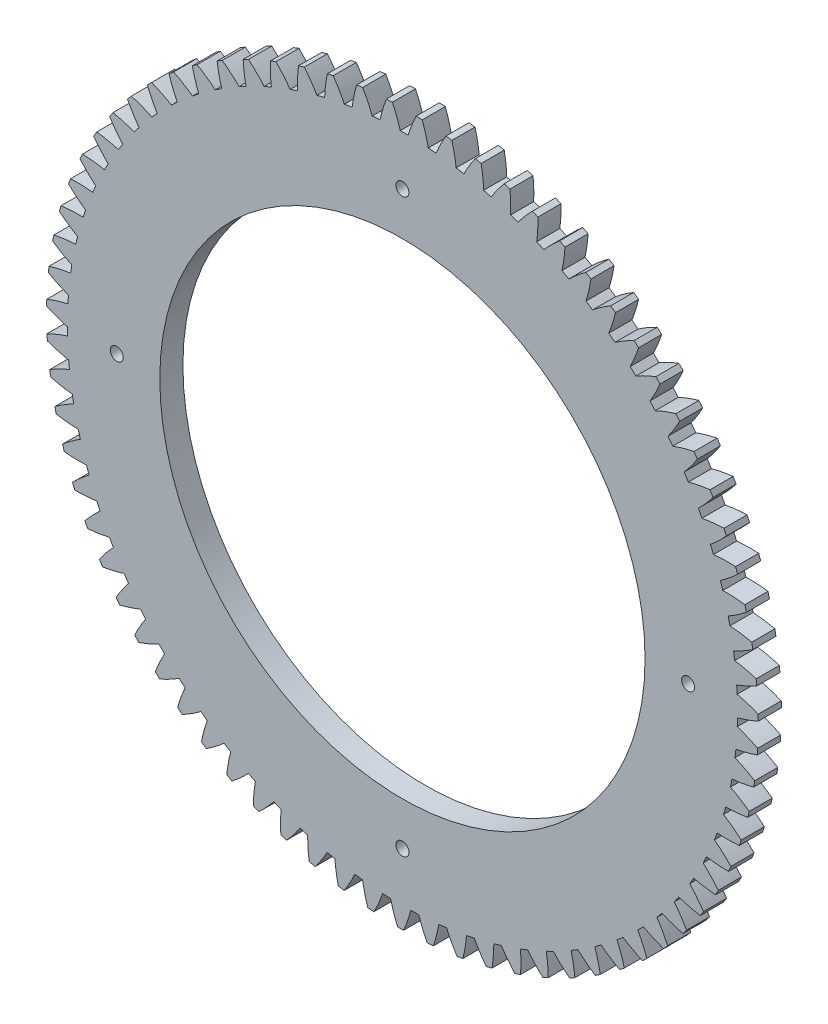
SolidWorks part; units mm, degrees
ref_plane "Front Plane" through (0, 0, 0) normal (0, 0, 1) x (1, 0, 0)
ref_plane "Top Plane" through (0, 0, 0) normal (0, 1, 0) x (1, 0, 0)
ref_plane "Right Plane" through (0, 0, 0) normal (1, 0, 0) x (0, 0, -1)
sketch "Sketch1" plane through (0, 0, 0) normal (0, 0, 1) x (1, 0, 0)
  circle A0 centre (0, 0) radius 78.5 construction
  circle A1 centre (0, 78.5) radius 1.7859
  circle A2 centre (78.5, 0) radius 1.7859
  circle A3 centre (0, -78.5) radius 1.7859
  circle A4 centre (-78.5, 0) radius 1.7859
  point P14 (0, 0)
  circle B0 centre (0, 0) radius 66.675
  arc B1 (-97.7746, 1.7328) -> (-92.073, -0.3661) centre (-81.8037, 36.3238) ccw
  arc B2 (-92.073, -0.3661) -> (-92.039, -2.5301) centre (0, 0) ccw
  arc B3 (-92.039, -2.5301) -> (-97.6718, -4.8073) centre (-80.6208, -38.8788) ccw
  arc B4 (-97.6718, -4.8073) -> (-97.5767, -6.4549) centre (0, 0) ccw
  arc B5 (-97.5767, -6.4549) -> (-91.7195, -8.0693) centre (-84.5564, 29.3513) ccw
  arc B6 (-91.7195, -8.0693) -> (-91.5045, -10.2228) centre (0, 0) ccw
  arc B7 (-91.5045, -10.2228) -> (-96.927, -12.9634) centre (-77.0847, -45.4887) ccw
  arc B8 (-96.927, -12.9634) -> (-96.6944, -14.5972) centre (0, 0) ccw
  arc B9 (-96.6944, -14.5972) -> (-90.7226, -15.7159) centre (-86.7159, 22.1729) ccw
  arc B10 (-90.7226, -15.7159) -> (-90.3281, -17.8438) centre (0, 0) ccw
  arc B11 (-90.3281, -17.8438) -> (-95.5023, -21.0285) centre (-73.008, -51.7794) ccw
  arc B12 (-95.5023, -21.0285) -> (-95.1338, -22.6372) centre (0, 0) ccw
  arc B13 (-95.1338, -22.6372) -> (-89.0893, -23.2522) centre (-88.2671, 14.8389) ccw
  arc B14 (-89.0893, -23.2522) -> (-88.5182, -25.3397) centre (0, 0) ccw
  arc B15 (-88.5182, -25.3397) -> (-93.4077, -28.9462) centre (-68.4191, -57.707) ccw
  arc B16 (-93.4077, -28.9462) -> (-92.9059, -30.5184) centre (0, 0) ccw
  arc B17 (-92.9059, -30.5184) -> (-86.8312, -30.6255) centre (-89.1992, 7.4009) ccw
  arc B18 (-86.8312, -30.6255) -> (-86.0874, -32.6579) centre (0, 0) ccw
  arc B19 (-86.0874, -32.6579) -> (-90.658, -36.6608) centre (-63.3504, -63.2298) ccw
  arc B20 (-90.658, -36.6608) -> (-90.0264, -38.1855) centre (0, 0) ccw
  arc B21 (-90.0264, -38.1855) -> (-83.964, -37.7839) centre (-89.5057, -0.0891) ccw
  arc B22 (-83.964, -37.7839) -> (-83.0527, -39.7469) centre (0, 0) ccw
  arc B23 (-83.0527, -39.7469) -> (-87.2723, -44.1183) centre (-57.8373, -68.309) ccw
  arc B24 (-87.2723, -44.1183) -> (-86.5154, -45.5848) centre (0, 0) ccw
  arc B25 (-86.5154, -45.5848) -> (-80.5078, -44.6773) centre (-89.1843, -7.5784) ccw
  arc B26 (-80.5078, -44.6773) -> (-79.4355, -46.5572) centre (0, 0) ccw
  arc B27 (-79.4355, -46.5572) -> (-83.2745, -51.2664) centre (-51.9185, -72.9092) ccw
  arc B28 (-83.2745, -51.2664) -> (-82.3975, -52.6644) centre (0, 0) ccw
  arc B29 (-82.3975, -52.6644) -> (-76.487, -51.2574) centre (-88.2374, -15.0146) ccw
  arc B30 (-76.487, -51.2574) -> (-75.2611, -53.0409) centre (0, 0) ccw
  arc B31 (-75.2611, -53.0409) -> (-78.6926, -58.0548) centre (-45.6355, -76.9979) ccw
  arc B32 (-78.6926, -58.0548) -> (-77.7017, -59.3745) centre (0, 0) ccw
  arc B33 (-77.7017, -59.3745) -> (-71.9296, -57.4779) centre (-86.6715, -22.3455) ccw
  arc B34 (-71.9296, -57.4779) -> (-70.5588, -59.1526) centre (0, 0) ccw
  arc B35 (-70.5588, -59.1526) -> (-73.5587, -64.436) centre (-39.0325, -80.5465) ccw
  arc B36 (-73.5587, -64.436) -> (-72.4608, -65.6682) centre (0, 0) ccw
  arc B37 (-72.4608, -65.6682) -> (-66.8677, -63.2952) centre (-84.4977, -29.5196) ccw
  arc B38 (-66.8677, -63.2952) -> (-65.3616, -64.8493) centre (0, 0) ccw
  arc B39 (-65.3616, -64.8493) -> (-67.9089, -70.3653) centre (-32.1556, -83.5302) ccw
  arc B40 (-67.9089, -70.3653) -> (-66.7117, -71.5013) centre (0, 0) ccw
  arc B41 (-66.7117, -71.5013) -> (-61.3368, -68.6686) centre (-81.7313, -36.4866) ccw
  arc B42 (-61.3368, -68.6686) -> (-59.7059, -70.0912) centre (0, 0) ccw
  arc B43 (-59.7059, -70.0912) -> (-61.7827, -75.801) centre (-25.0532, -85.9279) ccw
  arc B44 (-61.7827, -75.801) -> (-60.4947, -76.8328) centre (0, 0) ccw
  arc B45 (-60.4947, -76.8328) -> (-55.3756, -73.5603) centre (-78.3915, -43.1978) ccw
  arc B46 (-55.3756, -73.5603) -> (-53.6314, -74.8415) centre (0, 0) ccw
  arc B47 (-53.6314, -74.8415) -> (-55.2231, -80.7049) centre (-17.7751, -87.723) ccw
  arc B48 (-55.2231, -80.7049) -> (-53.8533, -81.6254) centre (0, 0) ccw
  arc B49 (-53.8533, -81.6254) -> (-49.0261, -77.936) centre (-74.5019, -49.6059) ccw
  arc B50 (-49.0261, -77.936) -> (-47.1807, -79.0667) centre (0, 0) ccw
  arc B51 (-47.1807, -79.0667) -> (-48.2763, -85.0429) centre (-10.3723, -88.9027) ccw
  arc B52 (-48.2763, -85.0429) -> (-46.8342, -85.8454) centre (0, 0) ccw
  arc B53 (-46.8342, -85.8454) -> (-42.3326, -81.765) centre (-70.0897, -55.6661) ccw
  arc B54 (-42.3326, -81.765) -> (-40.3991, -82.7374) centre (0, 0) ccw
  arc B55 (-40.3991, -82.7374) -> (-40.9907, -88.7843) centre (-2.8967, -89.4588) ccw
  arc B56 (-40.9907, -88.7843) -> (-39.4866, -89.4634) centre (0, 0) ccw
  arc B57 (-39.4866, -89.4634) -> (-35.3422, -85.0206) centre (-65.1858, -61.3358) ccw
  arc B58 (-35.3422, -85.0206) -> (-33.3342, -85.8278) centre (0, 0) ccw
  arc B59 (-33.3342, -85.8278) -> (-33.4177, -91.9029) centre (4.5992, -89.3875) ccw
  arc B60 (-33.4177, -91.9029) -> (-31.862, -92.4538) centre (0, 0) ccw
  arc B61 (-31.862, -92.4538) -> (-28.1039, -87.6798) centre (-59.8248, -66.5753) ccw
  arc B62 (-28.1039, -87.6798) -> (-26.0354, -88.3161) centre (0, 0) ccw
  arc B63 (-26.0354, -88.3161) -> (-25.6103, -94.3769) centre (12.0628, -88.6891) ccw
  arc B64 (-25.6103, -94.3769) -> (-24.0139, -94.7956) centre (0, 0) ccw
  arc B65 (-24.0139, -94.7956) -> (-20.6685, -89.7239) centre (-54.0441, -71.3478) ccw
  arc B66 (-20.6685, -89.7239) -> (-18.554, -90.1849) centre (0, 0) ccw
  arc B67 (-18.554, -90.1849) -> (-17.6232, -96.1889) centre (19.4418, -87.3687) ccw
  arc B68 (-17.6232, -96.1889) -> (-15.9974, -96.4726) centre (0, 0) ccw
  arc B69 (-15.9974, -96.4726) -> (-13.0881, -91.1388) centre (-47.8843, -75.6199) ccw
  arc B70 (-13.0881, -91.1388) -> (-10.9424, -91.4212) centre (0, 0) ccw
  arc B71 (-10.9424, -91.4212) -> (-9.5125, -97.3262) centre (26.6844, -85.4354) ccw
  arc B72 (-9.5125, -97.3262) -> (-7.8687, -97.4729) centre (0, 0) ccw
  arc B73 (-7.8687, -97.4729) -> (-5.4159, -91.9143) centre (-41.3887, -79.3615) ccw
  arc B74 (-5.4159, -91.9143) -> (-3.2541, -92.0162) centre (0, 0) ccw
  arc B75 (-3.2541, -92.0162) -> (-1.3351, -97.7809) centre (33.7399, -82.9029) ccw
  arc B76 (-1.3351, -97.7809) -> (0.3152, -97.7895) centre (0, 0) ccw
  arc B77 (0.3152, -97.7895) -> (2.2943, -92.0451) centre (-34.6027, -82.5465) ccw
  arc B78 (2.2943, -92.0451) -> (4.457, -91.9658) centre (0, 0) ccw
  arc B79 (4.457, -91.9658) -> (6.8517, -97.5497) centre (40.5587, -79.7889) ccw
  arc B80 (6.8517, -97.5497) -> (8.4969, -97.4202) centre (0, 0) ccw
  arc B81 (8.4969, -97.4202) -> (9.9884, -91.5303) centre (-27.574, -85.1525) ccw
  arc B82 (9.9884, -91.5303) -> (12.1369, -91.2703) centre (0, 0) ccw
  arc B83 (12.1369, -91.2703) -> (14.9904, -96.6342) centre (47.093, -76.1152) ccw
  arc B84 (14.9904, -96.6342) -> (16.619, -96.3675) centre (0, 0) ccw
  arc B85 (16.619, -96.3675) -> (17.6124, -90.3735) centre (-20.3519, -87.1612) ccw
  arc B86 (17.6124, -90.3735) -> (19.7316, -89.9346) centre (0, 0) ccw
  arc B87 (19.7316, -89.9346) -> (23.024, -95.0409) centre (53.297, -71.9076) ccw
  arc B88 (23.024, -95.0409) -> (24.6246, -94.6389) centre (0, 0) ccw
  arc B89 (24.6246, -94.6389) -> (25.1129, -88.5828) centre (-12.9871, -88.5585) ccw
  arc B90 (25.1129, -88.5828) -> (27.188, -87.9681) centre (0, 0) ccw
  arc B91 (27.188, -87.9681) -> (30.896, -92.781) centre (59.1272, -67.1956) ccw
  arc B92 (30.896, -92.781) -> (32.4574, -92.2464) centre (0, 0) ccw
  arc B93 (32.4574, -92.2464) -> (32.4372, -86.1708) centre (-5.5312, -89.3347) ccw
  arc B94 (32.4372, -86.1708) -> (34.4536, -85.3846) centre (0, 0) ccw
  arc B95 (34.4536, -85.3846) -> (38.5514, -89.8703) centre (64.5426, -62.0123) ccw
  arc B96 (38.5514, -89.8703) -> (40.0625, -89.2069) centre (0, 0) ccw
  arc B97 (40.0625, -89.2069) -> (39.534, -83.1543) centre (1.9636, -89.4842) ccw
  arc B98 (39.534, -83.1543) -> (41.4775, -82.2021) centre (0, 0) ccw
  arc B99 (41.4775, -82.2021) -> (45.9364, -86.3292) centre (69.5053, -56.394) ccw
  arc B100 (45.9364, -86.3292) -> (47.3867, -85.5417) centre (0, 0) ccw
  arc B101 (47.3867, -85.5417) -> (46.3536, -79.5545) centre (9.4445, -89.006) ccw
  arc B102 (46.3536, -79.5545) -> (48.2106, -78.4431) centre (0, 0) ccw
  arc B103 (48.2106, -78.4431) -> (52.9991, -82.1826) centre (73.9805, -50.3802) ccw
  arc B104 (52.9991, -82.1826) -> (54.3784, -81.2765) centre (0, 0) ccw
  arc B105 (54.3784, -81.2765) -> (52.8479, -75.3967) centre (16.8592, -87.9036) ccw
  arc B106 (52.8479, -75.3967) -> (54.6054, -74.1338) centre (0, 0) ccw
  arc B107 (54.6054, -74.1338) -> (59.6901, -77.4595) centre (77.9367, -44.013) ccw
  arc B108 (59.6901, -77.4595) -> (60.9888, -76.4412) centre (0, 0) ccw
  arc B109 (60.9888, -76.4412) -> (58.9716, -70.7101) centre (24.1557, -86.1846) ccw
  arc B110 (58.9716, -70.7101) -> (60.6173, -69.3045) centre (0, 0) ccw
  arc B111 (60.6173, -69.3045) -> (65.9624, -72.1931) centre (81.3463, -37.3371) ccw
  arc B112 (65.9624, -72.1931) -> (67.1713, -71.0697) centre (0, 0) ccw
  arc B113 (67.1713, -71.0697) -> (64.6817, -65.5275) centre (31.2827, -83.861) ccw
  arc B114 (64.6817, -65.5275) -> (66.2039, -63.9891) centre (0, 0) ccw
  arc B115 (66.2039, -63.9891) -> (71.772, -66.4204) centre (84.1853, -30.3992) ccw
  arc B116 (71.772, -66.4204) -> (72.8827, -65.1997) centre (0, 0) ccw
  arc B117 (72.8827, -65.1997) -> (69.938, -59.8853) centre (38.1903, -80.9492) ccw
  arc B118 (69.938, -59.8853) -> (71.3262, -58.2249) centre (0, 0) ccw
  arc B119 (71.3262, -58.2249) -> (77.0782, -60.1817) centre (86.4338, -23.2482) ccw
  arc B120 (77.0782, -60.1817) -> (78.0828, -58.8724) centre (0, 0) ccw
  arc B121 (78.0828, -58.8724) -> (74.7038, -53.823) centre (44.83, -77.4696) ccw
  arc B122 (74.7038, -53.823) -> (75.9482, -52.0523) centre (0, 0) ccw
  arc B123 (75.9482, -52.0523) -> (81.8438, -53.5209) centre (88.076, -15.9341) ccw
  arc B124 (81.8438, -53.5209) -> (82.7353, -52.1321) centre (0, 0) ccw
  arc B125 (82.7353, -52.1321) -> (78.9456, -47.3831) centre (51.1553, -73.4467) ccw
  arc B126 (78.9456, -47.3831) -> (80.0375, -45.5146) centre (0, 0) ccw
  arc B127 (80.0375, -45.5146) -> (86.0352, -46.4847) centre (89.1004, -8.5082) ccw
  arc B128 (86.0352, -46.4847) -> (86.8074, -45.0261) centre (0, 0) ccw
  arc B129 (86.8074, -45.0261) -> (82.6337, -40.611) centre (57.1217, -68.9085) ccw
  arc B130 (82.6337, -40.611) -> (83.5653, -38.6576) centre (0, 0) ccw
  arc B131 (83.5653, -38.6576) -> (89.6232, -39.1224) centre (89.4999, -1.0226) ccw
  arc B132 (89.6232, -39.1224) -> (90.2707, -37.6044) centre (0, 0) ccw
  arc B133 (90.2707, -37.6044) -> (85.7421, -33.5539) centre (62.6875, -63.887) ccw
  arc B134 (85.7421, -33.5539) -> (86.507, -31.5294) centre (0, 0) ccw
  arc B135 (86.507, -31.5294) -> (92.5826, -31.4857) centre (89.2716, 6.4702) ccw
  arc B136 (92.5826, -31.4857) -> (93.1007, -29.9188) centre (0, 0) ccw
  arc B137 (93.1007, -29.9188) -> (88.2491, -26.2615) centre (67.8136, -58.4174) ccw
  arc B138 (88.2491, -26.2615) -> (88.842, -24.1801) centre (0, 0) ccw
  arc B139 (88.842, -24.1801) -> (94.8925, -23.6282) centre (88.4171, 13.9175) ccw
  arc B140 (94.8925, -23.6282) -> (95.2778, -22.0234) centre (0, 0) ccw
  arc B141 (95.2778, -22.0234) -> (90.1371, -18.7849) centre (72.464, -52.538) ccw
  arc B142 (90.1371, -18.7849) -> (90.5537, -16.6612) centre (0, 0) ccw
  arc B143 (90.5537, -16.6612) -> (96.5369, -15.6049) centre (86.9424, 21.2673) ccw
  arc B144 (96.5369, -15.6049) -> (96.7865, -13.9735) centre (0, 0) ccw
  arc B145 (96.7865, -13.9735) -> (91.3929, -11.1766) centre (76.6061, -46.2901) ccw
  arc B146 (91.3929, -11.1766) -> (91.6303, -9.0254) centre (0, 0) ccw
  arc B147 (91.6303, -9.0254) -> (97.5041, -7.4722) centre (84.8579, 28.4678) ccw
  arc B148 (97.5041, -7.4722) -> (97.6163, -5.8257) centre (0, 0) ccw
  arc B149 (97.6163, -5.8257) -> (92.0076, -3.4898) centre (80.2109, -39.7176) ccw
  arc B150 (92.0076, -3.4898) -> (92.0642, -1.3264) centre (0, 0) ccw
  arc B151 (92.0642, -1.3264) -> (97.7874, 0.713) centre (82.1781, 35.4687) ccw
  arc B152 (97.7874, 0.713) -> (97.7614, 2.3631) centre (0, 0) ccw
  arc B153 (97.7614, 2.3631) -> (91.9769, 4.2214) centre (83.2531, -32.8664) ccw
  arc B154 (91.9769, 4.2214) -> (91.8523, 6.382) centre (0, 0) ccw
  arc B155 (91.8523, 6.382) -> (97.3848, 8.8931) centre (78.922, 42.2208) ccw
  arc B156 (97.3848, 8.8931) -> (97.2208, 10.5353) centre (0, 0) ccw
  arc B157 (97.2208, 10.5353) -> (91.3011, 11.903) centre (85.7113, -25.7847) ccw
  arc B158 (91.3011, 11.903) -> (90.9961, 14.0456) centre (0, 0) ccw
  arc B159 (90.9961, 14.0456) -> (96.2991, 17.0109) centre (75.1122, 48.6767) ccw
  arc B160 (96.2991, 17.0109) -> (95.9983, 18.6336) centre (0, 0) ccw
  arc B161 (95.9983, 18.6336) -> (89.9849, 19.5012) centre (87.5683, -18.5221) ccw
  arc B162 (89.9849, 19.5012) -> (89.5017, 21.6107) centre (0, 0) ccw
  arc B163 (89.5017, 21.6107) -> (94.5379, 25.0093) centre (70.7757, 54.7913) ccw
  arc B164 (94.5379, 25.0093) -> (94.1024, 26.6011) centre (0, 0) ccw
  arc B165 (94.1024, 26.6011) -> (88.0375, 26.9625) centre (88.8111, -11.1296) ccw
  arc B166 (88.0375, 26.9625) -> (87.3794, 29.0243) centre (0, 0) ccw
  arc B167 (87.3794, 29.0243) -> (92.1136, 32.8323) centre (65.9426, 60.5214) ccw
  arc B168 (92.1136, 32.8323) -> (91.5465, 34.3821) centre (0, 0) ccw
  arc B169 (91.5465, 34.3821) -> (85.4725, 34.2347) centre (89.4309, -3.6591) ccw
  arc B170 (85.4725, 34.2347) -> (84.6443, 36.2342) centre (0, 0) ccw
  arc B171 (84.6443, 36.2342) -> (89.0432, 40.425) centre (60.647, 65.8271) ccw
  arc B172 (89.0432, 40.425) -> (88.3484, 41.922) centre (0, 0) ccw
  arc B173 (88.3484, 41.922) -> (82.3081, 41.2668) centre (89.4234, 3.8371) ccw
  arc B174 (82.3081, 41.2668) -> (81.3154, 43.19) centre (0, 0) ccw
  arc B175 (81.3154, 43.19) -> (85.3483, 47.7342) centre (54.9261, 70.6711) ccw
  arc B176 (85.3483, 47.7342) -> (84.5306, 49.1677) centre (0, 0) ccw
  arc B177 (84.5306, 49.1677) -> (78.5663, 48.0095) centre (88.7887, 11.3064) ccw
  arc B178 (78.5663, 48.0095) -> (77.4162, 49.8428) centre (0, 0) ccw
  arc B179 (77.4162, 49.8428) -> (81.0547, 54.7086) centre (48.8198, 75.0193) ccw
  arc B180 (81.0547, 54.7086) -> (80.1199, 56.0686) centre (0, 0) ccw
  arc B181 (80.1199, 56.0686) -> (74.2734, 54.4153) centre (87.5312, 18.6964) ccw
  arc B182 (74.2734, 54.4153) -> (72.974, 56.146) centre (0, 0) ccw
  arc B183 (72.974, 56.146) -> (76.1925, 61.2992) centre (42.3712, 78.8414) ccw
  arc B184 (76.1925, 61.2992) -> (75.1472, 62.5763) centre (0, 0) ccw
  arc B185 (75.1472, 62.5763) -> (69.4596, 60.4395) centre (85.6598, 25.9553) ccw
  arc B186 (69.4596, 60.4395) -> (68.0199, 62.0554) centre (0, 0) ccw
  arc B187 (68.0199, 62.0554) -> (70.7959, 67.4598) centre (35.6253, 82.1104) ccw
  arc B188 (70.7959, 67.4598) -> (69.6474, 68.6449) centre (0, 0) ccw
  arc B189 (69.6474, 68.6449) -> (64.1585, 66.0398) centre (83.1875, 33.0321) ccw
  arc B190 (64.1585, 66.0398) -> (62.5886, 67.5295) centre (0, 0) ccw
  arc B191 (62.5886, 67.5295) -> (64.9027, 73.1473) centre (28.6295, 84.8034) ccw
  arc B192 (64.9027, 73.1473) -> (63.659, 74.2321) centre (0, 0) ccw
  arc B193 (63.659, 74.2321) -> (58.4074, 71.1768) centre (80.1317, 39.8772) ccw
  arc B194 (58.4074, 71.1768) -> (56.7184, 72.53) centre (0, 0) ccw
  arc B195 (56.7184, 72.53) -> (58.5543, 78.3217) centre (21.4329, 86.9017) ccw
  arc B196 (58.5543, 78.3217) -> (57.2242, 79.2986) centre (0, 0) ccw
  arc B197 (57.2242, 79.2986) -> (52.2467, 75.8146) centre (76.5138, 46.4426) ccw
  arc B198 (52.2467, 75.8146) -> (50.4503, 77.0217) centre (0, 0) ccw
  arc B199 (50.4503, 77.0217) -> (51.7951, 82.9467) centre (14.086, 88.3904) ccw
  arc B200 (51.7951, 82.9467) -> (50.388, 83.8089) centre (0, 0) ccw
  arc B201 (50.388, 83.8089) -> (45.7194, 79.9206) centre (72.3592, 52.6822) ccw
  arc B202 (45.7194, 79.9206) -> (43.8284, 80.9731) centre (0, 0) ccw
  arc B203 (43.8284, 80.9731) -> (44.6727, 86.9899) centre (6.6403, 89.2591) ccw
  arc B204 (44.6727, 86.9899) -> (43.1983, 87.7314) centre (0, 0) ccw
  arc B205 (43.1983, 87.7314) -> (38.8715, 83.466) centre (67.6971, 58.5523) ccw
  arc B206 (38.8715, 83.466) -> (36.899, 84.3566) centre (0, 0) ccw
  arc B207 (36.899, 84.3566) -> (37.2369, 90.4229) centre (-0.852, 89.5017) ccw
  arc B208 (37.2369, 90.4229) -> (35.7056, 91.0384) centre (0, 0) ccw
  arc B209 (35.7056, 91.0384) -> (31.7509, 86.426) centre (62.5602, 64.0117) ccw
  arc B210 (31.7509, 86.426) -> (29.7108, 87.1484) centre (0, 0) ccw
  arc B211 (29.7108, 87.1484) -> (29.5399, 93.2217) centre (-8.3383, 89.1165) ccw
  arc B212 (29.5399, 93.2217) -> (27.9625, 93.7069) centre (0, 0) ccw
  arc B213 (27.9625, 93.7069) -> (24.4076, 88.7797) centre (56.9844, 69.0221) ccw
  arc B214 (24.4076, 88.7797) -> (22.3142, 89.3289) centre (0, 0) ccw
  arc B215 (22.3142, 89.3289) -> (21.6357, 95.3666) centre (-15.7661, 88.1062) ccw
  arc B216 (21.6357, 95.3666) -> (20.0232, 95.7181) centre (0, 0) ccw
  arc B217 (20.0232, 95.7181) -> (16.8931, 90.5107) centre (51.0089, 73.5484) ccw
  arc B218 (16.8931, 90.5107) -> (14.7611, 90.8828) centre (0, 0) ccw
  arc B219 (14.7611, 90.8828) -> (13.5798, 96.8425) centre (-23.0834, 86.4779) ccw
  arc B220 (13.5798, 96.8425) -> (11.9435, 97.0579) centre (0, 0) ccw
  arc B221 (11.9435, 97.0579) -> (9.2601, 91.6069) centre (44.6757, 77.5587) ccw
  arc B222 (9.2601, 91.6069) -> (7.1045, 91.7992) centre (0, 0) ccw
  arc B223 (7.1045, 91.7992) -> (5.4286, 97.6392) centre (-30.2387, 84.2431) ccw
  arc B224 (5.4286, 97.6392) -> (3.7801, 97.7169) centre (0, 0) ccw
  arc B225 (3.7801, 97.7169) -> (1.5622, 92.0605) centre (38.029, 81.0251) ccw
  arc B226 (1.5622, 92.0605) -> (-0.602, 92.0718) centre (0, 0) ccw
  arc B227 (-0.602, 92.0718) -> (-2.7607, 97.751) centre (-37.1819, 81.4173) ccw
  arc B228 (-2.7607, 97.751) -> (-4.4099, 97.6905) centre (0, 0) ccw
  arc B229 (-4.4099, 97.6905) -> (-6.1467, 91.8683) centre (31.1157, 83.9231) ccw
  arc B230 (-6.1467, 91.8683) -> (-8.3042, 91.6985) centre (0, 0) ccw
  arc B231 (-8.3042, 91.6985) -> (-10.9306, 97.1772) centre (-43.8644, 78.0205) ccw
  arc B232 (-10.9306, 97.1772) -> (-12.569, 96.9789) centre (0, 0) ccw
  arc B233 (-12.569, 96.9789) -> (-13.8125, 91.0318) centre (23.984, 86.2325) ccw
  arc B234 (-13.8125, 91.0318) -> (-15.9482, 90.682) centre (0, 0) ccw
  arc B235 (-15.9482, 90.682) -> (-19.0239, 95.9217) centre (-50.2391, 74.0764) ccw
  arc B236 (-19.0239, 95.9217) -> (-20.6399, 95.587) centre (0, 0) ccw
  arc B237 (-20.6399, 95.587) -> (-21.3814, 89.5567) centre (16.6842, 87.937) ccw
  arc B238 (-21.3814, 89.5567) -> (-23.4804, 89.0295) centre (0, 0) ccw
  arc B239 (-23.4804, 89.0295) -> (-26.9837, 93.9934) centre (-56.2615, 69.6127) ccw
  arc B240 (-26.9837, 93.9934) -> (-28.566, 93.5247) centre (0, 0) ccw
  arc B241 (-28.566, 93.5247) -> (-28.8003, 87.4535) centre (9.2673, 89.0247) ccw
  arc B242 (-28.8003, 87.4535) -> (-30.8478, 86.7524) centre (0, 0) ccw
  arc B243 (-30.8478, 86.7524) -> (-34.7542, 91.4058) centre (-61.8892, 64.6607) ccw
  arc B244 (-34.7542, 91.4058) -> (-36.2918, 90.8063) centre (0, 0) ccw
  arc B245 (-36.2918, 90.8063) -> (-36.0172, 84.7368) centre (1.7854, 89.4879) ccw
  arc B246 (-36.0172, 84.7368) -> (-37.9989, 83.8669) centre (0, 0) ccw
  arc B247 (-37.9989, 83.8669) -> (-42.281, 88.1771) centre (-67.0828, 59.2552) ccw
  arc B248 (-42.281, 88.1771) -> (-43.763, 87.451) centre (0, 0) ccw
  arc B249 (-43.763, 87.451) -> (-42.9815, 81.4258) centre (-5.709, 89.3235) ccw
  arc B250 (-42.9815, 81.4258) -> (-44.8834, 80.3931) centre (0, 0) ccw
  arc B251 (-44.8834, 80.3931) -> (-49.5111, 84.3299) centre (-71.8059, 53.434) ccw
  arc B252 (-49.5111, 84.3299) -> (-50.9272, 83.4823) centre (0, 0) ccw
  arc B253 (-50.9272, 83.4823) -> (-49.6443, 77.5436) centre (-13.1634, 88.5325) ccw
  arc B254 (-49.6443, 77.5436) -> (-51.4531, 76.3554) centre (0, 0) ccw
  arc B255 (-51.4531, 76.3554) -> (-56.394, 79.8911) centre (-76.0253, 47.238) ccw
  arc B256 (-56.394, 79.8911) -> (-57.7342, 78.9281) centre (0, 0) ccw
  arc B257 (-57.7342, 78.9281) -> (-55.9589, 73.1176) centre (-20.5254, 87.1205) ccw
  arc B258 (-55.9589, 73.1176) -> (-57.6619, 71.7821) centre (0, 0) ccw
  arc B259 (-57.6619, 71.7821) -> (-62.8814, 74.892) centre (-79.7114, 40.7107) ccw
  arc B260 (-62.8814, 74.892) -> (-64.1363, 73.8202) centre (0, 0) ccw
  arc B261 (-64.1363, 73.8202) -> (-61.8809, 68.1786) centre (-27.7435, 85.0974) ccw
  arc B262 (-61.8809, 68.1786) -> (-63.4663, 66.7053) centre (0, 0) ccw
  arc B263 (-63.4663, 66.7053) -> (-68.9277, 69.3676) centre (-82.8384, 33.8979) ccw
  arc B264 (-68.9277, 69.3676) -> (-70.0885, 68.1945) centre (0, 0) ccw
  arc B265 (-70.0885, 68.1945) -> (-67.369, 62.7614) centre (-34.767, 82.4775) ccw
  arc B266 (-67.369, 62.7614) -> (-68.8255, 61.1607) centre (0, 0) ccw
  arc B267 (-68.8255, 61.1607) -> (-74.4904, 63.3566) centre (-85.3844, 26.8473) ccw
  arc B268 (-74.4904, 63.3566) -> (-75.549, 62.0905) centre (0, 0) ccw
  arc B269 (-75.549, 62.0905) -> (-72.3844, 56.904) centre (-41.5466, 79.279) ccw
  arc B270 (-72.3844, 56.904) -> (-73.7019, 55.187) centre (0, 0) ccw
  arc B271 (-73.7019, 55.187) -> (-79.5307, 56.9012) centre (-87.3315, 19.6083) ccw
  arc B272 (-79.5307, 56.9012) -> (-80.4797, 55.5509) centre (0, 0) ccw
  arc B273 (-80.4797, 55.5509) -> (-76.8922, 50.6475) centre (-48.0348, 75.5244) ccw
  arc B274 (-76.8922, 50.6475) -> (-78.0613, 48.8262) centre (0, 0) ccw
  arc B275 (-78.0613, 48.8262) -> (-84.0132, 50.0467) centre (-88.666, 12.2318) ccw
  arc B276 (-84.0132, 50.0467) -> (-84.8458, 48.6218) centre (0, 0) ccw
  arc B277 (-84.8458, 48.6218) -> (-80.8606, 44.0357) centre (-54.186, 71.2401) ccw
  arc B278 (-80.8606, 44.0357) -> (-81.8732, 42.123) centre (0, 0) ccw
  arc B279 (-81.8732, 42.123) -> (-87.9063, 42.8411) centre (-89.3786, 4.7696) ccw
  arc B280 (-87.9063, 42.8411) -> (-88.6168, 41.3515) centre (0, 0) ccw
  arc B281 (-88.6168, 41.3515) -> (-84.2618, 37.115) centre (-59.9572, 66.4561) ccw
  arc B282 (-84.2618, 37.115) -> (-85.1108, 35.1243) centre (0, 0) ccw
  arc B283 (-85.1108, 35.1243) -> (-91.1829, 35.335) centre (-89.4642, -2.7262) ccw
  arc B284 (-91.1829, 35.335) -> (-91.7662, 33.7912) centre (0, 0) ccw
  arc B285 (-91.7662, 33.7912) -> (-87.072, 29.934) centre (-65.3078, 61.2059) ccw
  arc B286 (-87.072, 29.934) -> (-87.7515, 27.8792) centre (0, 0) ccw
  arc B287 (-87.7515, 27.8792) -> (-93.8199, 27.5811) centre (-88.9223, -10.2028) ccw
  arc B288 (-93.8199, 27.5811) -> (-94.2719, 25.9939) centre (0, 0) ccw
  arc B289 (-94.2719, 25.9939) -> (-89.2714, 22.543) centre (-70.2004, 55.5264) ccw
  arc B290 (-89.2714, 22.543) -> (-89.7766, 20.4386) centre (0, 0) ccw
  arc B291 (-89.7766, 20.4386) -> (-95.7987, 19.6338) centre (-87.7567, -17.6078) ccw
  arc B292 (-95.7987, 19.6338) -> (-96.1164, 18.0143) centre (0, 0) ccw
  arc B293 (-96.1164, 18.0143) -> (-90.8447, 14.9939) centre (-74.6005, 49.4575) ccw
  arc B294 (-90.8447, 14.9939) -> (-91.172, 12.8546) centre (0, 0) ccw
  arc B295 (-91.172, 12.8546) -> (-97.1057, 11.5487) centre (-85.9755, -24.8894) ccw
  arc B296 (-97.1057, 11.5487) -> (-97.2867, 9.9083) centre (0, 0) ccw
  arc B297 (-97.2867, 9.9083) -> (-91.7807, 7.3396) centre (-78.4773, 43.0416) ccw
  arc B298 (-91.7807, 7.3396) -> (-91.9279, 5.1804) centre (0, 0) ccw
  arc B299 (-91.9279, 5.1804) -> (-97.7315, 3.3826) centre (-83.5913, -31.9963) ccw
  arc B300 (-97.7315, 3.3826) -> (-97.7746, 1.7328) centre (0, 0) ccw
  dimension "D1" = 157
  dimension "D2" = 3.5719
  dimension "D3" = 4
sketch_block_instance "HG_Gear-1"
sketch_block "HG_Gear"
extrude "Boss-Extrude1" add sketch "Sketch1" along normal blind 6.35
